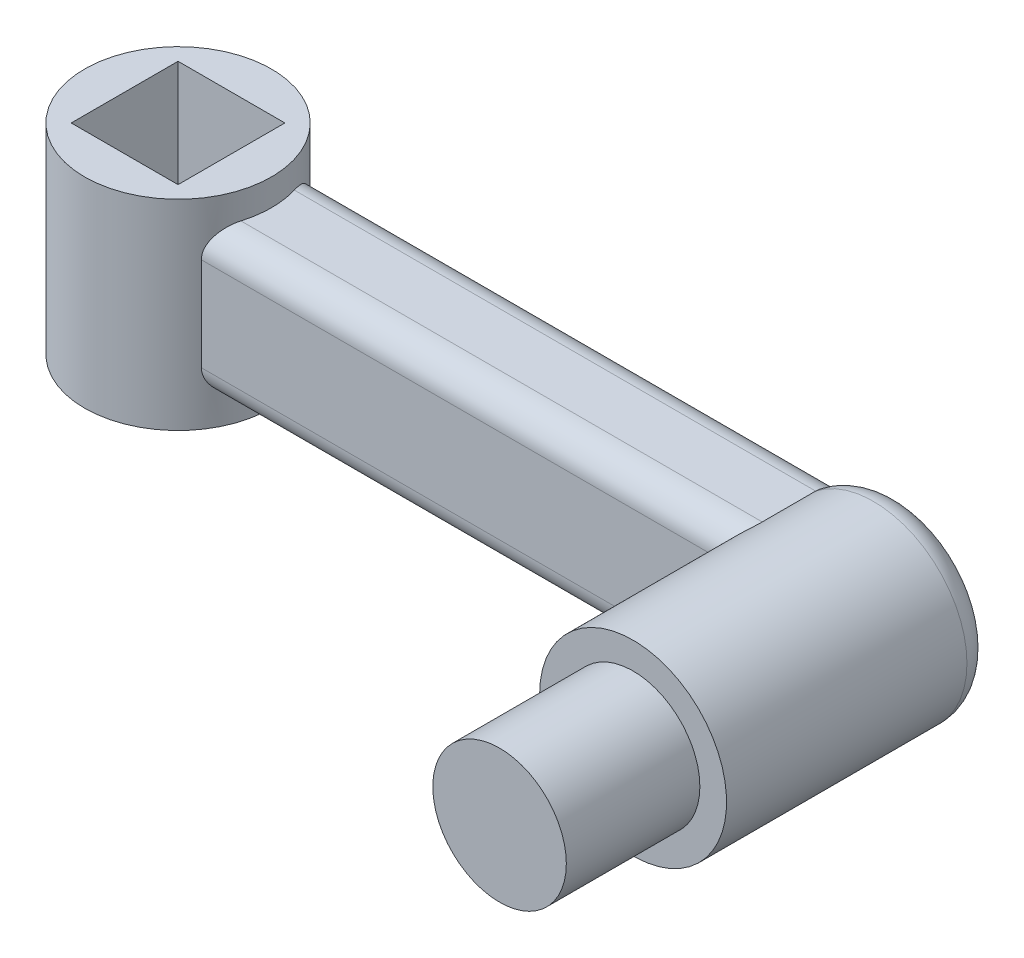
SolidWorks part; units mm, degrees
material "6061 Alloy"
ref_plane "Front Plane" through (0, 0, 0) normal (0, 0, 1) x (1, 0, 0)
ref_plane "Top Plane" through (0, 0, 0) normal (0, 1, 0) x (1, 0, 0)
ref_plane "Right Plane" through (0, 0, 0) normal (1, 0, 0) x (0, 0, -1)
other "Center of Mass"
sketch "Sketch1" plane through (0, 0, 0) normal (0, 1, 0) x (1, 0, 0)
  circle A0 centre (0, 0) radius 35
  dimension "D1" = 70
extrude "Boss-Extrude1" add sketch "Sketch1" along normal blind 75
sketch "Sketch2" plane through (0, 75, 0) normal (0, 1, 0) x (1, 0, 0)
  line L1 (-20, -20) -> (20, -20)
  line L2 (-20, -20) -> (-20, 20)
  line L3 (-20, 20) -> (20, 20)
  line L4 (20, -20) -> (20, 20)
  line L5 (-20, -20) -> (20, 20) construction
  line L6 (-20, 20) -> (20, -20) construction
  point P0 (0, 0)
  dimension "D1" = 40
extrude "Cut-Extrude1" cut sketch "Sketch2" against normal through all
sketch "Sketch3" plane through (0, 75, 0) normal (0, 1, 0) x (1, 0, 0)
  line L0 (0, 0) -> (207.256, 0) construction
  line L2 (228.7228, -20) -> (28.7228, -20)
  line L3 (228.7228, -20) -> (228.7228, 20)
  line L4 (228.7228, 20) -> (28.7228, 20)
  line L5 (28.7228, -20) -> (28.7228, 20)
  line L6 (228.7228, -20) -> (28.7228, 20) construction
  line L7 (228.7228, 20) -> (28.7228, -20) construction
  circle A0 centre (0, 0) radius 35 construction
  point P3 (128.7228, 0)
  dimension "D1" = 200
  dimension "D2" = 40
extrude "Boss-Extrude2" add sketch "Sketch3" against normal blind 55 from offset 10 offset against normal yes
sketch "Sketch5" plane through (0, 0, -20) normal (0, 0, -1) x (-1, 0, 0)
  line L0 (-28.7228, 37.5) -> (-250.3734, 37.5) construction
  line L1 (-28.7228, 10) -> (-28.7228, 65) construction
  circle A0 centre (-250.3734, 37.5) radius 35
  dimension "D1" = 70
extrude "Boss-Extrude3" add sketch "Sketch5" against normal blind 100
sketch "Sketch8" plane through (0, 0, 80) normal (0, 0, 1) x (1, 0, 0)
  circle A0 centre (250.3734, 37.5) radius 25
  dimension "D1" = 50
extrude "Boss-Extrude5" add sketch "Sketch8" along normal blind 50
fillet "Fillet1" radius 10 4 edges at (128.7228, 10, -20) (128.7228, 10, 20) (128.7228, 65, -20) (128.7228, 65, 20)
fillet "Fillet2" radius 10 1 edges at (285.3734, 37.5, -20)
move or copy body "Body-Move/Copy1" bodies to move or copy 106 copy no translate (-250, -37.5, 0) parameters "D1"=250, "D2"=37.5, "D3"=0
